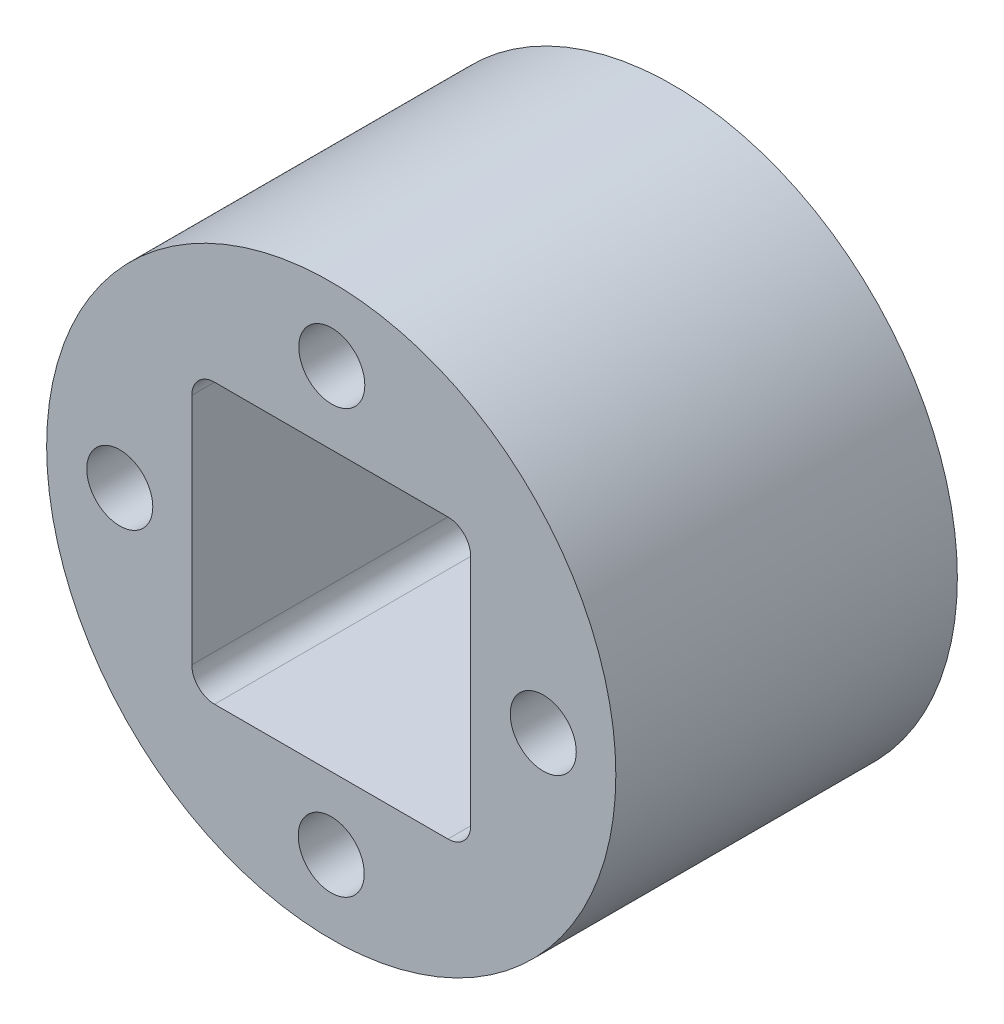
SolidWorks part; units mm, degrees
ref_plane "Front Plane" through (0, 0, 0) normal (0, 0, 1) x (1, 0, 0)
ref_plane "Top Plane" through (0, 0, 0) normal (0, 1, 0) x (1, 0, 0)
ref_plane "Right Plane" through (0, 0, 0) normal (1, 0, 0) x (0, 0, -1)
sketch "Sketch1" plane through (0, 0, 0) normal (0, 0, 1) x (1, 0, 0)
  circle A0 centre (0, 0) radius 12.5
  dimension "D2" = 25
extrude "Boss-Extrude1" add sketch "Sketch1" along normal mid plane 15
sketch "Sketch8" plane through (0, 0, 7.5) normal (0, 0, 1) x (1, 0, 0)
  line L2 (-6.125, 6.125) -> (6.125, 6.125)
  line L3 (-6.125, 6.125) -> (-6.125, -6.125)
  line L4 (-6.125, -6.125) -> (6.125, -6.125)
  line L5 (6.125, 6.125) -> (6.125, -6.125)
  line L6 (-6.125, 6.125) -> (6.125, -6.125) construction
  line L7 (-6.125, -6.125) -> (6.125, 6.125) construction
  point P5 (0, 0)
  point P14 (0, 0)
  dimension "D1" = 12.25
extrude "Cut-Extrude3" cut sketch "Sketch8" against normal up to next
sketch "Sketch9" plane through (0, 0, 7.5) normal (0, 0, 1) x (1, 0, 0)
  line L0 (8.25, 0) -> (-8.25, 0) construction
  line L1 (6.125, -6.125) -> (6.125, 6.125) construction
  circle A0 centre (9.3125, 0) radius 1.45
  circle A1 centre (0, -9.2875) radius 1.45
  circle A2 centre (-9.2875, 0.025) radius 1.45
  circle A3 centre (0.025, 9.3125) radius 1.45
  point P14 (0.0125, 0.0125)
  dimension "D1" = 2.9
  dimension "D2" = 3.1875
  dimension "D3" = 4
extrude "Cut-Extrude4" cut sketch "Sketch9" against normal blind 10
fillet "Fillet1" radius 1 4 edges at (-6.125, 6.125, 0) (6.125, 6.125, 0) (6.125, -6.125, 0) (-6.125, -6.125, 0)
equation "\"drumDiameter\"= 25"
equation "\"D2@Sketch1\"=\"drumDiameter\""
equation "\"drumLength\"= 15"
equation "\"foamThickness\"= 5"
equation "\"drumAbove\"= 0.6"
equation "\"holderThicc\"= 4"
equation "\"D1@Boss-Extrude1\"=\"drumLength\""
equation "\"squareBarLength\"= 12.25"
equation "\"D1@Sketch8\"=\"squareBarLength\""
equation "\"D2@Sketch9\"=(\"drumDiameter\"/2-\"squareBarLength\"/2)/2"
